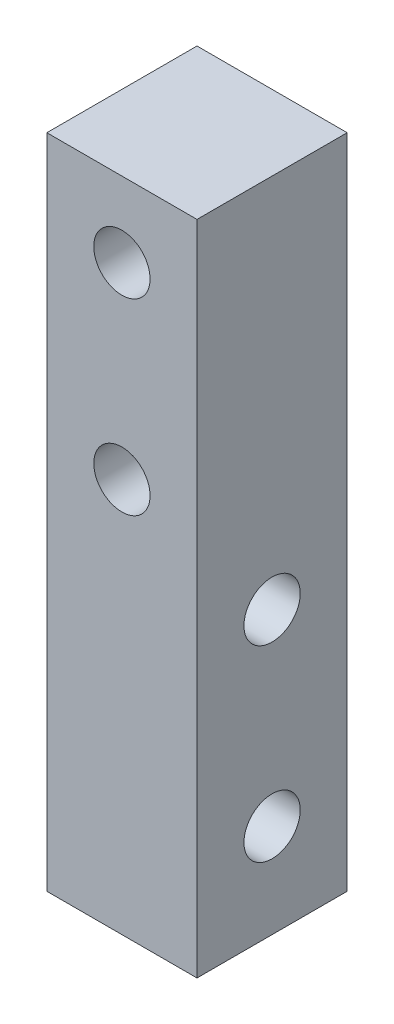
SolidWorks part; units mm, degrees
material "ABS PC"
ref_plane "Front Plane" through (0, 0, 0) normal (0, 0, 1) x (1, 0, 0)
ref_plane "Top Plane" through (0, 0, 0) normal (0, 1, 0) x (1, 0, 0)
ref_plane "Right Plane" through (0, 0, 0) normal (1, 0, 0) x (0, 0, -1)
sketch "Sketch1" plane through (0, 0, 0) normal (0, 1, 0) x (1, 0, 0)
  line L1 (-4, 4) -> (4, 4)
  line L2 (-4, 4) -> (-4, -4)
  line L3 (-4, -4) -> (4, -4)
  line L4 (4, 4) -> (4, -4)
  line L5 (-4, 4) -> (4, -4) construction
  line L6 (-4, -4) -> (4, 4) construction
  point P0 (0, 0)
  dimension "D1" = 8
  dimension "D2" = 8
extrude "Boss-Extrude1" add sketch "Sketch1" along normal blind 35
sketch "Sketch2" plane through (0, 0, -4) normal (0, 0, -1) x (-1, 0, 0)
  line L0 (-4, 35) -> (4, 35) construction
  circle A0 centre (0, 31) radius 1.5
  circle A1 centre (0, 21) radius 1.5
  dimension "D1" = 3
  dimension "D2" = 4
  dimension "D3" = 10
extrude "Cut-Extrude1" cut sketch "Sketch2" against normal through all
sketch "Sketch3" plane through (4, 0, 0) normal (1, 0, 0) x (0, 0, -1)
  line L0 (-4, 0) -> (4, 0) construction
  circle A0 centre (0, 15) radius 1.5
  circle A1 centre (0, 5) radius 1.5
  point P4 (0, 0)
  point P7 (0, 0)
  dimension "D1" = 3
  dimension "D2" = 10
  dimension "D3" = 5
extrude "Cut-Extrude2" cut sketch "Sketch3" against normal through all
